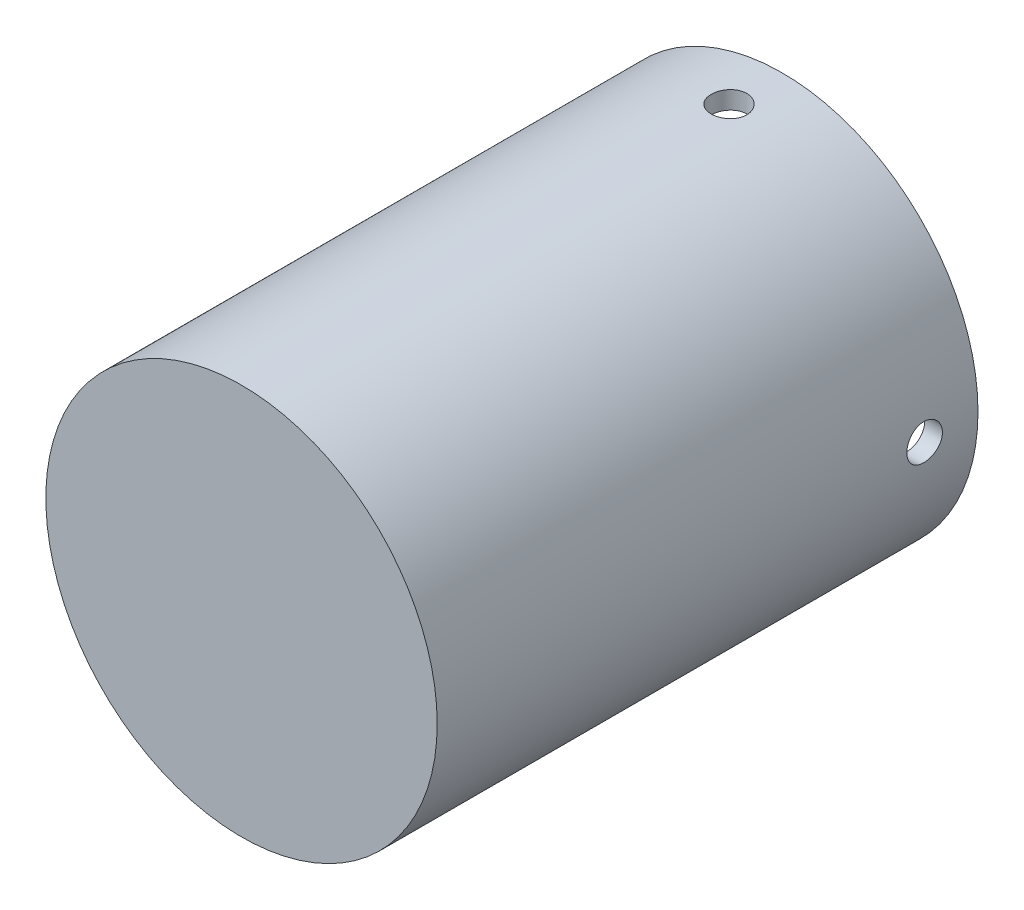
SolidWorks part; units mm, degrees
ref_plane "Front Plane" through (0, 0, 0) normal (0, 0, 1) x (1, 0, 0)
ref_plane "Top Plane" through (0, 0, 0) normal (0, 1, 0) x (1, 0, 0)
ref_plane "Right Plane" through (0, 0, 0) normal (1, 0, 0) x (0, 0, -1)
sketch "Sketch1" plane through (0, 0, 0) normal (0, 0, 1) x (1, 0, 0)
  circle A0 centre (0, 0) radius 55
extrude "Cup" add sketch "Sketch1" along normal blind 152
sketch "Sketch2" plane through (0, 0, 0) normal (0, 0, 1) x (1, 0, 0)
  circle A0 centre (0, 0) radius 50
extrude "Cavity" cut sketch "Sketch2" along normal blind 148
ref_plane "Plane_x49_5" through (49.5, 0, 0) normal (1, 0, 0) x (0, 0, -1)
sketch "Sketch3" plane through (49.5, 0, 0) normal (1, 0, 0) x (0, 0, -1)
  circle A0 centre (-15, 0) radius 5
extrude "Vent" cut sketch "Sketch3" along normal blind 6
ref_axis "Axis_Z" through (0, 0, -7.6) along (0, 0, 1)
pattern_circular "Vents" count 4 over 360 about axis through (0, 0, -7.6) along (0, 0, 1) of "Vent"
